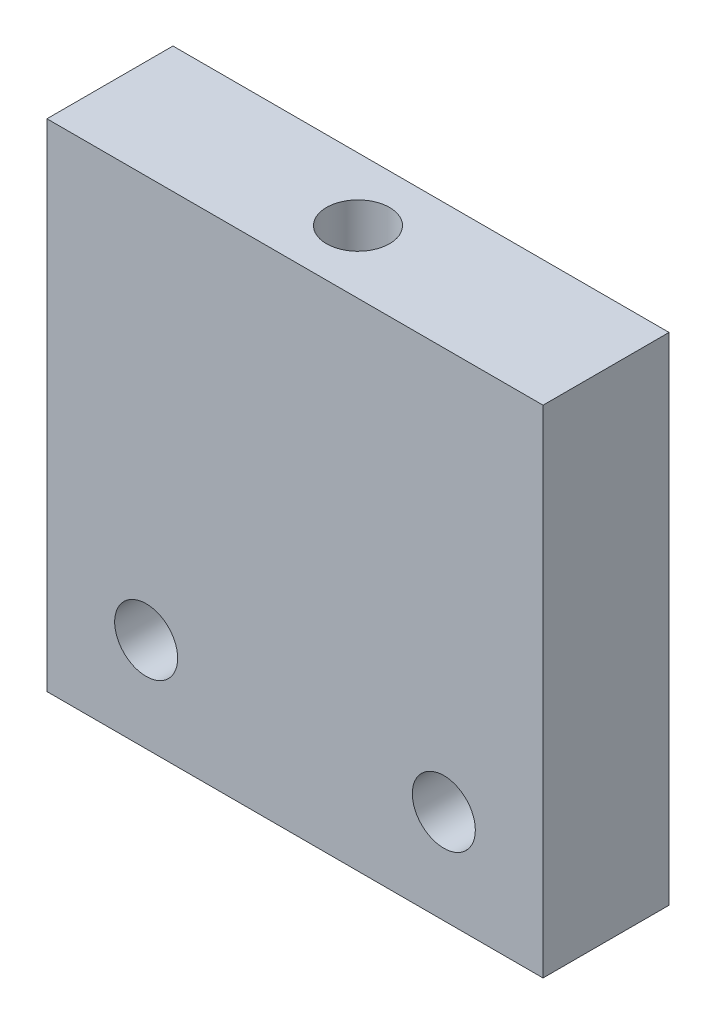
SolidWorks part; units mm, degrees
ref_plane "Front Plane" through (0, 0, 0) normal (0, 0, 1) x (1, 0, 0)
ref_plane "Top Plane" through (0, 0, 0) normal (0, 1, 0) x (1, 0, 0)
ref_plane "Right Plane" through (0, 0, 0) normal (1, 0, 0) x (0, 0, -1)
sketch "Sketch1" plane through (0, 0, 0) normal (0, 1, 0) x (1, 0, 0)
  line L1 (-41.4145, 0) -> (8.5855, 0)
  line L2 (-41.4145, 0) -> (-41.4145, -12.7)
  line L3 (-41.4145, -12.7) -> (8.5855, -12.7)
  line L4 (8.5855, 0) -> (8.5855, -12.7)
  dimension "D1" = 50
  dimension "D2" = 12.7
extrude "Boss-Extrude1" add sketch "Sketch1" along normal blind 50
sketch "Sketch4" plane through (0, 0, 12.7) normal (0, 0, 1) x (1, 0, 0)
  line L0 (-41.4145, 0) -> (8.5855, 0) construction
  line L1 (8.5855, 50) -> (8.5855, 0) construction
  line L2 (-41.4145, 50) -> (-41.4145, 0) construction
  circle A0 centre (-1.4145, 9.5) radius 3.175
  circle A1 centre (-31.4145, 9.5) radius 3.175
  point P10 (0, 0)
  point P11 (0, 0)
  dimension "D1" = 9.5
  dimension "D3" = 9.5
  dimension "D2" = 10
  dimension "D4" = 10
extrude "Cut-Extrude2" cut sketch "Sketch4" against normal through all
sketch "Sketch5" plane through (0, 50, 0) normal (0, 1, 0) x (1, 0, 0)
  line L0 (8.5855, -6.35) -> (-41.4145, -6.35) construction
  line L1 (8.5855, -12.7) -> (8.5855, 0) construction
  line L2 (-41.4145, 0) -> (-41.4145, -12.7) construction
  line L3 (-16.4145, -12.7) -> (-16.4145, 0) construction
  line L4 (-41.4145, -12.7) -> (8.5855, -12.7) construction
  line L5 (8.5855, 0) -> (-41.4145, 0) construction
  circle A0 centre (-16.4145, -6.35) radius 3.175
extrude "Cut-Extrude3" cut sketch "Sketch5" against normal blind 30
sketch "Sketch6" plane through (0, 0, 0) normal (0, 0, -1) x (-1, 0, 0)
  line L0 (16.4145, 0) -> (16.4145, 50) construction
  line L1 (-8.5855, 0) -> (41.4145, 0) construction
  line L2 (-8.5855, 50) -> (41.4145, 50) construction
  line L3 (41.4145, 25) -> (-8.5855, 25) construction
  line L4 (41.4145, 50) -> (41.4145, 0) construction
  line L5 (-8.5855, 50) -> (-8.5855, 0) construction
  line L7 (18.9145, 20) -> (13.9145, 20)
  line L8 (18.9145, 20) -> (18.9145, 30)
  line L9 (18.9145, 30) -> (13.9145, 30)
  line L10 (13.9145, 20) -> (13.9145, 30)
  line L11 (18.9145, 20) -> (13.9145, 30) construction
  line L12 (18.9145, 30) -> (13.9145, 20) construction
  point P12 (16.4145, 25)
  dimension "D1" = 5
  dimension "D2" = 10
extrude "Boss-Extrude3" add sketch "Sketch6" along normal blind 5
